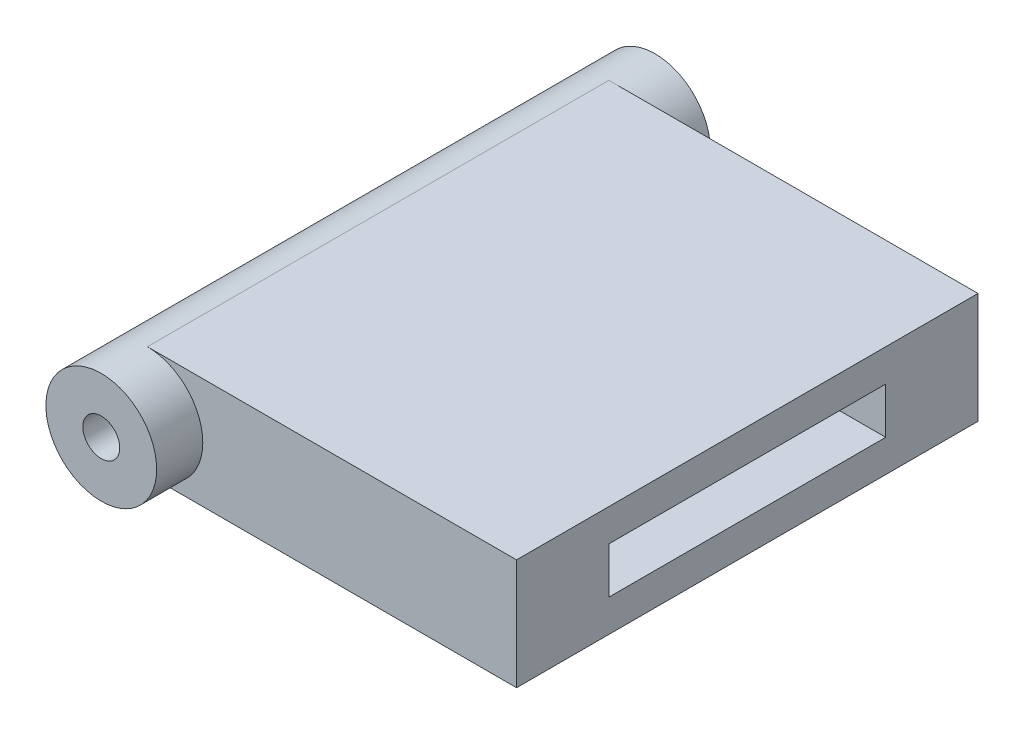
SolidWorks part; units mm, degrees
ref_plane "Front" through (0, 0, 0) normal (0, 0, 1) x (1, 0, 0)
ref_plane "Top" through (0, 0, 0) normal (0, 1, 0) x (1, 0, 0)
ref_plane "Right" through (0, 0, 0) normal (1, 0, 0) x (0, 0, -1)
sketch "Sketch4" plane through (0, 0, 0) normal (0, 0, 1) x (1, 0, 0)
  circle A0 centre (0, 0) radius 2.54
  circle A1 centre (0, 0) radius 7.62
  dimension "D1" = 5.08
  dimension "D2" = 5.08
extrude "Boss-Extrude1" add sketch "Sketch4" along normal blind 76.2
sketch "Sketch5" plane through (0, 0, 0) normal (1, 0, 0) x (0, 0, -1)
  line L0 (0, 7.62) -> (-76.2, 7.62) construction
  line L1 (0, 7.62) -> (-76.2, 7.62)
  line L2 (-76.2, -7.62) -> (0, -7.62) construction
  line L3 (-69.85, 7.62) -> (-6.35, 7.62)
  line L4 (-69.85, 7.62) -> (-69.85, -7.62)
  line L5 (-69.85, -7.62) -> (-6.35, -7.62)
  line L6 (-6.35, 7.62) -> (-6.35, -7.62)
  point P8 (-38.1, 7.62)
  dimension "D1" = 63.5
  dimension "D2" = 31.75
extrude "Boss-Extrude2" add sketch "Sketch5" along normal blind 50.8 contours L6 L1 L4 L5
sketch "Sketch6" plane through (50.8, 0, 0) normal (1, 0, 0) x (0, 0, -1)
  line L0 (55, 0) -> (-55, 0) construction
  line L1 (-57.15, 3.175) -> (-19.05, 3.175)
  line L2 (-57.15, 3.175) -> (-57.15, -3.175)
  line L3 (-57.15, -3.175) -> (-19.05, -3.175)
  line L4 (-19.05, 3.175) -> (-19.05, -3.175)
  line L5 (-57.15, 3.175) -> (-19.05, -3.175) construction
  line L6 (-57.15, -3.175) -> (-19.05, 3.175) construction
  point P0 (-38.1, 0)
  dimension "D1" = 38.1
  dimension "D2" = 6.35
extrude "Cut-Extrude1" cut sketch "Sketch6" against normal blind 25.4
sketch "Sketch7" plane through (0, 0, 0) normal (0, 0, 1) x (1, 0, 0)
  circle A0 centre (0, 0) radius 2.54
extrude "Cut-Extrude2" cut sketch "Sketch7" against normal through all and the other way through all
